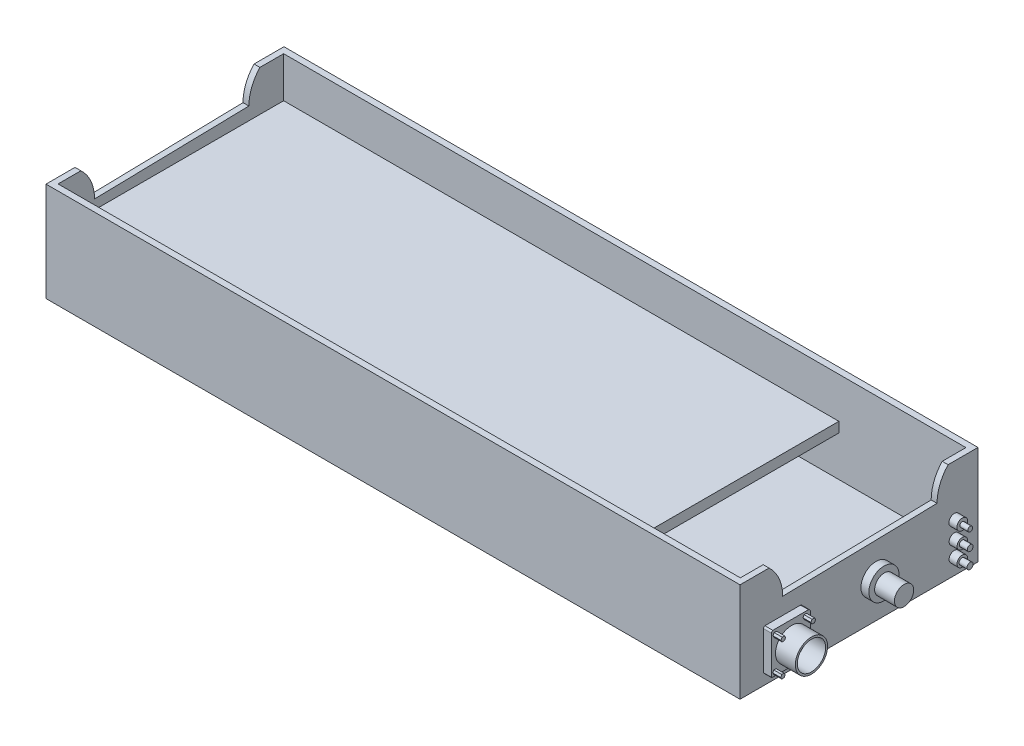
SolidWorks part; units mm, degrees
ref_plane "Front Plane" through (0, 0, 0) normal (0, 0, 1) x (1, 0, 0)
ref_plane "Top Plane" through (0, 0, 0) normal (0, 1, 0) x (1, 0, 0)
ref_plane "Right Plane" through (0, 0, 0) normal (1, 0, 0) x (0, 0, -1)
sketch "Sketch1" plane through (0, 0, 0) normal (0, 1, 0) x (1, 0, 0)
  line L1 (-87.5, 30) -> (87.5, 30)
  line L2 (-87.5, 30) -> (-87.5, -30)
  line L3 (-87.5, -30) -> (87.5, -30)
  line L4 (87.5, 30) -> (87.5, -30)
  line L5 (-87.5, 30) -> (87.5, -30) construction
  line L6 (-87.5, -30) -> (87.5, 30) construction
  point P0 (0, 0)
  dimension "D1" = 175
  dimension "D2" = 60
extrude "Boss-Extrude1" add sketch "Sketch1" along normal blind 25
sketch "Sketch2" plane through (0, 25, 0) normal (0, 1, 0) x (1, 0, 0)
  line L1 (-86.0187, 28.4392) -> (86.0187, 28.4392)
  line L2 (-86.0187, 28.4392) -> (-86.0187, -28.4392)
  line L3 (-86.0187, -28.4392) -> (86.0187, -28.4392)
  line L4 (86.0187, 28.4392) -> (86.0187, -28.4392)
  line L5 (-86.0187, 28.4392) -> (86.0187, -28.4392) construction
  line L6 (-86.0187, -28.4392) -> (86.0187, 28.4392) construction
  point P0 (0, 0)
extrude "Cut-Extrude2" cut sketch "Sketch2" against normal blind 23
sketch "Sketch3" plane through (87.5, 0, 0) normal (1, 0, 0) x (0, 0, -1)
  line L0 (-30, 25) -> (-30, 0) construction
  line L1 (30, 25) -> (30, 0) construction
  line L2 (-19.242, 17.1148) -> (19.673, 17.9513)
  line L3 (-30, 27.8728) -> (-30, 39.0255)
  line L4 (-30, 39.0255) -> (30, 38.1581)
  line L5 (30, 38.1581) -> (30, 25)
  arc A0 (-19.242, 17.1148) -> (-30, 27.8728) centre (-30, 17.1148) ccw
  arc A1 (30, 28.2783) -> (19.673, 17.9513) centre (30, 17.9513) ccw
  line M3 (30, 25) -> (-30, 25)
extrude "Cut-Extrude4" cut sketch "Sketch3" against normal through all contours A1 A0 L2 M3
sketch "Sketch5" plane through (-86.0187, 0, 0) normal (1, 0, 0) x (0, 0, -1)
  line L0 (28.4392, 2) -> (28.4392, 25) construction
  line L1 (-28.1805, 14.7226) -> (28.4392, 14.7226)
  line L2 (-28.1805, 14.7226) -> (-28.1805, 12.1794)
  line L3 (-28.1805, 12.1794) -> (28.4392, 12.1794)
  line L4 (28.4392, 14.7226) -> (28.4392, 12.1794)
extrude "Boss-Extrude2" add sketch "Sketch5" along normal blind 140
sketch "Sketch6" plane through (87.5, 0, 0) normal (1, 0, 0) x (0, 0, -1)
  line L1 (-23.7399, 12.934) -> (-14.7499, 12.934)
  line L2 (-24.078, 12.4502) -> (-24.078, 2.8751)
  line L3 (-23.969, 2.7016) -> (-14.4274, 2.7016)
  line L4 (-14.2965, 12.5446) -> (-14.2965, 2.8146)
  arc A3 (-14.4274, 2.7016) -> (-14.2965, 2.8146) centre (-14.4703, 2.8836) ccw
  arc A4 (-24.078, 2.8751) -> (-23.969, 2.7016) centre (-23.9329, 2.8452) ccw
  arc A5 (-14.2965, 12.5446) -> (-14.7499, 12.934) centre (-14.8873, 12.3153) ccw
  arc A6 (-23.7399, 12.934) -> (-24.078, 12.4502) centre (-23.6334, 12.4996) ccw
  point P0 (-19.1823, 7.8178)
  point P2 (-24.0807, 12.4996)
  point P4 (-23.6364, 12.4989)
  point P8 (-24.0777, 2.8971)
  point P9 (-24.078, 2.8751)
extrude "Boss-Extrude3" add sketch "Sketch6" along normal blind 2
sketch "Sketch7" plane through (89.5, 0, 0) normal (1, 0, 0) x (0, 0, -1)
  circle A0 centre (-18.9918, 7.5485) radius 4.0699
  circle A1 centre (-18.9918, 7.5485) radius 3.5736
extrude "Boss-Extrude4" add sketch "Sketch7" along normal blind 5
sketch "Sketch8" plane through (89.5, 0, 0) normal (1, 0, 0) x (0, 0, -1)
  line L1 (-22.7916, 11.2119) -> (-22.4866, 11.742)
  line L2 (-22.4866, 11.742) -> (-22.7932, 12.2713)
  line L3 (-22.7932, 12.2713) -> (-23.4048, 12.2703)
  line L4 (-23.4048, 12.2703) -> (-23.7098, 11.7402)
  line L5 (-23.7098, 11.7402) -> (-23.4032, 11.211)
  line L6 (-23.4032, 11.211) -> (-22.7916, 11.2119)
  line L7 (-15.2143, 11.3537) -> (-14.9211, 11.8827)
  line L8 (-14.9211, 11.8827) -> (-15.2326, 12.4011)
  line L9 (-15.2326, 12.4011) -> (-15.8374, 12.3905)
  line L10 (-15.8374, 12.3905) -> (-16.1306, 11.8615)
  line L11 (-16.1306, 11.8615) -> (-15.8191, 11.3431)
  line L12 (-15.8191, 11.3431) -> (-15.2143, 11.3537)
  line L13 (-22.6144, 3.649) -> (-22.9033, 4.1494)
  line L14 (-22.9033, 4.1494) -> (-23.4811, 4.1494)
  line L15 (-23.4811, 4.1494) -> (-23.77, 3.649)
  line L16 (-23.77, 3.649) -> (-23.4811, 3.1485)
  line L17 (-23.4811, 3.1485) -> (-22.9033, 3.1485)
  line L18 (-22.9033, 3.1485) -> (-22.6144, 3.649)
  line L19 (-14.9839, 3.0843) -> (-14.6872, 3.5216)
  line L20 (-14.6872, 3.5216) -> (-14.9176, 3.9973)
  line L21 (-14.9176, 3.9973) -> (-15.4447, 4.0356)
  line L22 (-15.4447, 4.0356) -> (-15.7415, 3.5982)
  line L23 (-15.7415, 3.5982) -> (-15.5111, 3.1226)
  line L24 (-15.5111, 3.1226) -> (-14.9839, 3.0843)
  circle A0 centre (-23.0982, 11.7411) radius 0.5297 construction
  circle A1 centre (-15.5259, 11.8721) radius 0.5238 construction
  circle A2 centre (-23.1922, 3.649) radius 0.5004 construction
  circle A3 centre (-15.2143, 3.5599) radius 0.4577 construction
extrude "Boss-Extrude6" add sketch "Sketch8" along normal blind 2
sketch "Sketch9" plane through (87.5, 0, 0) normal (1, 0, 0) x (0, 0, -1)
  circle A0 centre (4.2871, 9.1518) radius 3.8037
extrude "Boss-Extrude7" add sketch "Sketch9" along normal blind 2
sketch "Sketch10" plane through (89.5, 0, 0) normal (1, 0, 0) x (0, 0, -1)
  circle A0 centre (4.363, 8.9798) radius 2.4308
  point P2 (4.3281, 9.2829)
  point P3 (4.363, 8.9798)
extrude "Boss-Extrude8" add sketch "Sketch10" along normal blind 5
sketch "Sketch11" plane through (87.5, 0, 0) normal (1, 0, 0) x (0, 0, -1)
  circle A0 centre (24.0404, 12.1934) radius 1.37
  circle A1 centre (24.0404, 8.0167) radius 1.3138
  circle A2 centre (24.0404, 4.1593) radius 1.3312
extrude "Boss-Extrude9" add sketch "Sketch11" along normal blind 2
sketch "Sketch12" plane through (89.5, 0, 0) normal (1, 0, 0) x (0, 0, -1)
  circle A0 centre (24.0404, 12.1447) radius 0.6136
  circle A1 centre (24.0404, 8.0167) radius 0.7365
  circle A2 centre (23.9936, 4.1339) radius 0.775
  point P7 (23.9936, 4.1339)
  point P8 (24.0404, 12.1447)
extrude "Boss-Extrude10" add sketch "Sketch12" along normal blind 2
